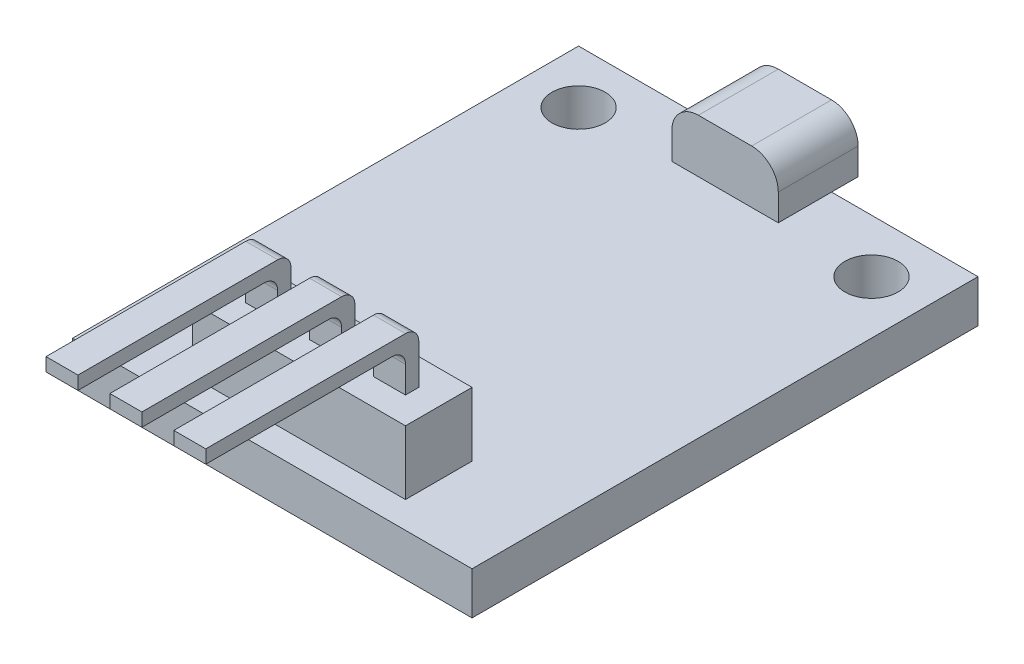
SolidWorks part; units mm, degrees
ref_plane "Plano frontal" through (0, 0, 0) normal (0, 0, 1) x (1, 0, 0)
ref_plane "Plano superior" through (0, 0, 0) normal (0, 1, 0) x (1, 0, 0)
ref_plane "Plano direito" through (0, 0, 0) normal (1, 0, 0) x (0, 0, -1)
sketch "Esboço1" plane through (0, 0, 0) normal (0, 1, 0) x (1, 0, 0)
  line L0 (-7.5, 7.5) -> (7.5, 7.5) construction
  line L1 (7.5, -9.5) -> (-7.5, -9.5)
  line L2 (7.5, -9.5) -> (7.5, 9.5)
  line L3 (7.5, 9.5) -> (-7.5, 9.5)
  line L4 (-7.5, -9.5) -> (-7.5, 9.5)
  line L5 (7.5, -9.5) -> (-7.5, 9.5) construction
  line L6 (7.5, 9.5) -> (-7.5, -9.5) construction
  circle A0 centre (-5.5, 7.5) radius 1
  circle A1 centre (5.5, 7.5) radius 1
  point P0 (0, 0)
  dimension "D3" = 2
  dimension "D5" = 2
  dimension "D6" = 2
  dimension "D1" = 15
  dimension "D2" = 19
  dimension "D4" = 2
extrude "Ressalto-extrusão1" add sketch "Esboço1" along normal blind 1.6
sketch "Esboço3" plane through (0, 1.6, 0) normal (0, 1, 0) x (1, 0, 0)
  line L0 (0, 0) -> (0, 9.5) construction
  line L1 (7.5, 9.5) -> (-7.5, 9.5) construction
  line L3 (-2, 7.5) -> (2, 7.5)
  line L4 (-2, 7.5) -> (-2, 10.5)
  line L5 (-2, 10.5) -> (2, 10.5)
  line L6 (2, 7.5) -> (2, 10.5)
  line L7 (-2, 7.5) -> (2, 10.5) construction
  line L8 (-2, 10.5) -> (2, 7.5) construction
  point P7 (0, 9)
  dimension "D1" = 1
  dimension "D2" = 4
  dimension "D3" = 3
extrude "Ressalto-extrusão2" add sketch "Esboço3" along normal blind 2
fillet "Filete1" radius 1 2 edges at (-2, 3.6, -9) (2, 3.6, -9)
sketch "Esboço4" plane through (0, 1.6, 0) normal (0, 1, 0) x (1, 0, 0)
  line L0 (0, -9.5) -> (0, 0) construction
  line L1 (-7.5, -9.5) -> (7.5, -9.5) construction
  line L3 (4, -6) -> (-4, -6)
  line L4 (4, -6) -> (4, -8.5)
  line L5 (4, -8.5) -> (-4, -8.5)
  line L6 (-4, -6) -> (-4, -8.5)
  line L7 (4, -6) -> (-4, -8.5) construction
  line L8 (4, -8.5) -> (-4, -6) construction
  point P5 (0, -7.25)
  dimension "D1" = 8
  dimension "D2" = 2.5
  dimension "D3" = 1
extrude "Ressalto-extrusão3" add sketch "Esboço4" along normal blind 2.4
sketch "Esboço5" plane through (0, 0, 0) normal (1, 0, 0) x (0, 0, -1)
  line L0 (-7.25, 4) -> (-7.25, 5.75) construction
  line L1 (-8.5, 4) -> (-6, 4) construction
  line L2 (-7.25, 5.75) -> (-15, 5.75) construction
  line L3 (-7.5, 4) -> (-7.5, 5)
  line L4 (-8, 5.5) -> (-15, 5.5)
  line L5 (-15, 5.5) -> (-15, 6)
  line L6 (-15, 6) -> (-7.5, 6)
  line L7 (-7, 5.5) -> (-7, 4)
  line L8 (-7.5, 4) -> (-7, 4)
  arc A0 (-7.5, 6) -> (-7, 5.5) centre (-7.5, 5.5) cw
  arc A1 (-7.5, 5) -> (-8, 5.5) centre (-8, 5) ccw
  point P13 (-7, 6)
  dimension "D7" = 0.5
  dimension "D1" = 0.25
  dimension "D2" = 0.25
  dimension "D3" = 0.25
  dimension "D4" = 0.25
  dimension "D5" = 8
  dimension "D6" = 2
extrude "Ressalto-extrusão4" add sketch "Esboço5" along normal mid plane 6
sketch "Esboço6" plane through (0, 6, 0) normal (0, 1, 0) x (1, 0, 0)
  line L0 (3, -7) -> (-3, -7) construction
  line L1 (-1.8, -7) -> (-0.6, -7)
  line L2 (-1.8, -7) -> (-1.8, -15)
  line L3 (-1.8, -15) -> (-0.6, -15)
  line L4 (-0.6, -7) -> (-0.6, -15)
  line L5 (3, -15) -> (-3, -15) construction
  line L6 (-3, -7) -> (-1.8, -7) construction
  line L7 (0.6, -7) -> (1.8, -7)
  line L8 (0.6, -7) -> (0.6, -15)
  line L9 (0.6, -15) -> (1.8, -15)
  line L10 (1.8, -7) -> (1.8, -15)
  line L11 (1.8, -7) -> (3, -7) construction
  line L12 (-0.6, -7) -> (0.6, -7) construction
extrude "Corte-extrusão1" cut sketch "Esboço6" against normal up to surface (2 mm away)
sketch "Esboço7" plane through (0, 0, 0) normal (0, -1, 0) x (1, 0, 0)
  line L0 (0, 9.5) -> (0, -9.5) construction
  line L1 (-7.5, 9.5) -> (7.5, 9.5) construction
  line L2 (7.5, -9.5) -> (-7.5, -9.5) construction
  line L4 (3, -6) -> (-3, -6)
  line L5 (3, -6) -> (3, 8)
  line L6 (3, 8) -> (-3, 8)
  line L7 (-3, -6) -> (-3, 8)
  line L8 (3, -6) -> (-3, 8) construction
  line L9 (3, 8) -> (-3, -6) construction
  point P6 (0, 1)
  dimension "D1" = 6
  dimension "D2" = 14
  dimension "D3" = 1.5
extrude "Ressalto-extrusão5" add sketch "Esboço7" along normal blind 1.5
